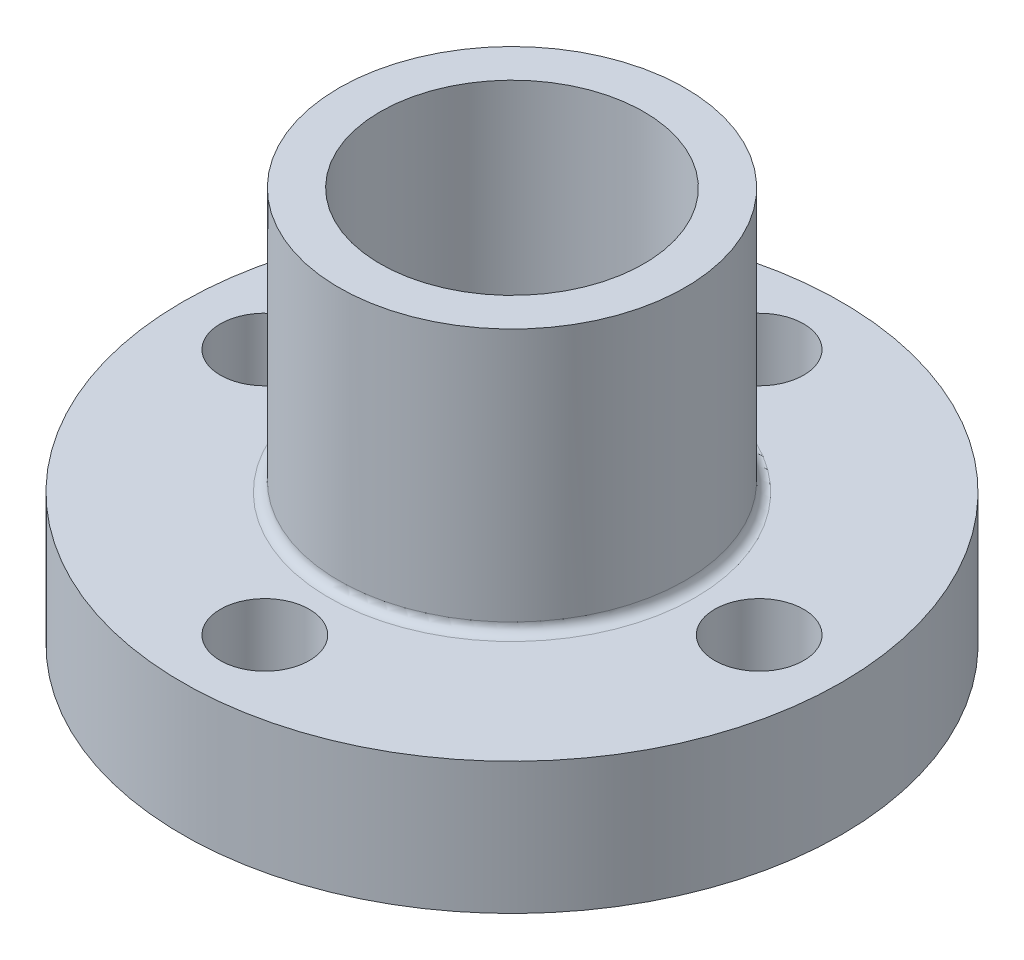
SolidWorks part; units mm, degrees
material "Brass"
ref_plane "Front" through (0, 0, 0) normal (0, 0, 1) x (1, 0, 0)
ref_plane "Top" through (0, 0, 0) normal (0, 1, 0) x (1, 0, 0)
ref_plane "Right" through (0, 0, 0) normal (1, 0, 0) x (0, 0, -1)
sketch "Sketch2" plane through (0, 0, 0) normal (0, 0, 1) x (1, 0, 0)
  line L0 (0, 0) -> (10, 0)
  line L1 (10, 0) -> (10, 4)
  line L2 (10, 4) -> (5.25, 4)
  line L3 (5.25, 4) -> (5.25, 12)
  line L4 (5.25, 12) -> (0, 12)
  line L5 (0, 12) -> (0, 0)
  line L6 (4, 12) -> (4, 0)
  dimension "D1" = 4
  dimension "D2" = 4
  dimension "D3" = 1.25
  dimension "D4" = 4.75
  dimension "D5" = 12
revolve "Revolve1" add sketch "Sketch2" angle 360 about L5
sketch "Sketch3" plane through (0, 4, 0) normal (0, 1, 0) x (1, 0, 0)
  circle A0 centre (7.5, 0) radius 1.35
  circle A1 centre (0, -7.5) radius 1.35
  circle A2 centre (-7.5, 0) radius 1.35
  circle A3 centre (0, 7.5) radius 1.35
  point P12 (0, 0)
  dimension "D1" = 2.7
  dimension "D2" = 7.5
  dimension "D3" = 4
extrude "Cut-Extrude1" cut sketch "Sketch3" against normal blind 10
fillet "Fillet1" radius 0.3 1 edges at (-5.25, 4, 0)
